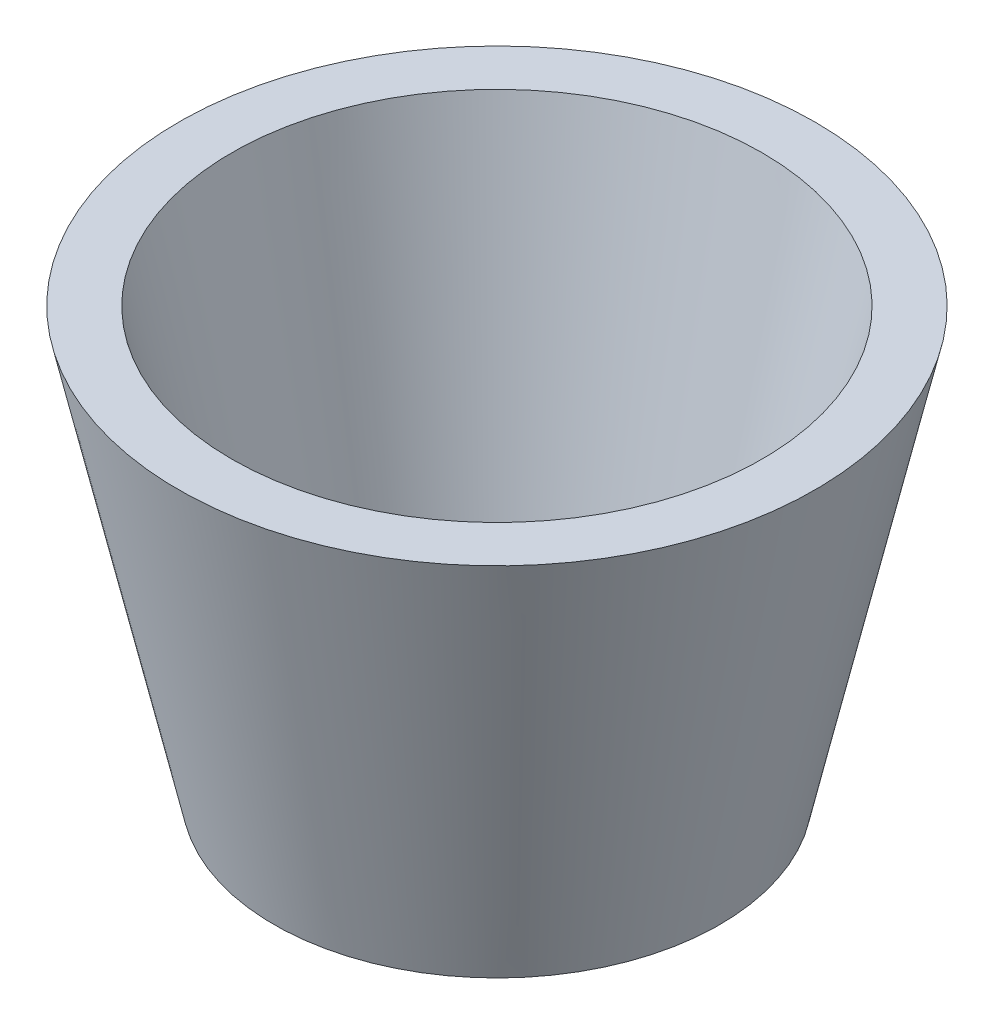
SolidWorks part; units mm, degrees
ref_plane "Front Plane" through (0, 0, 0) normal (0, 0, 1) x (1, 0, 0)
ref_plane "Top Plane" through (0, 0, 0) normal (0, 1, 0) x (1, 0, 0)
ref_plane "Right Plane" through (0, 0, 0) normal (1, 0, 0) x (0, 0, -1)
sketch "Sketch1" plane through (0, 0, 0) normal (0, 0, 1) x (1, 0, 0)
  line L0 (0, 0) -> (0, 373.549) construction
  line L1 (20, 0) -> (20, 218.8924) construction
  line L2 (42, 0) -> (42, 218.8924) construction
  line L3 (60, 0) -> (60, 218.8924) construction
  line L10 (20, 0) -> (42, 0)
  line L11 (42, 0) -> (60, 80)
  line L12 (60, 80) -> (50, 80)
  line L13 (50, 80) -> (34.25, 10)
  line L14 (34.25, 10) -> (20, 10)
  line L16 (6, 0) -> (6, 37.3375) construction
  line L17 (20, 10) -> (6, 10)
  line L18 (6, 10) -> (6, 0)
  line L19 (6, 0) -> (20, 0)
  dimension "D1" = 42
  dimension "D2" = 60
  dimension "D3" = 80
  dimension "D4" = 10
  dimension "D5" = 20
  dimension "D6" = 10
  dimension "D7" = 14.25
  dimension "D8" = 6
revolve "Revolve2" add sketch "Sketch1" angle 360 about L0
